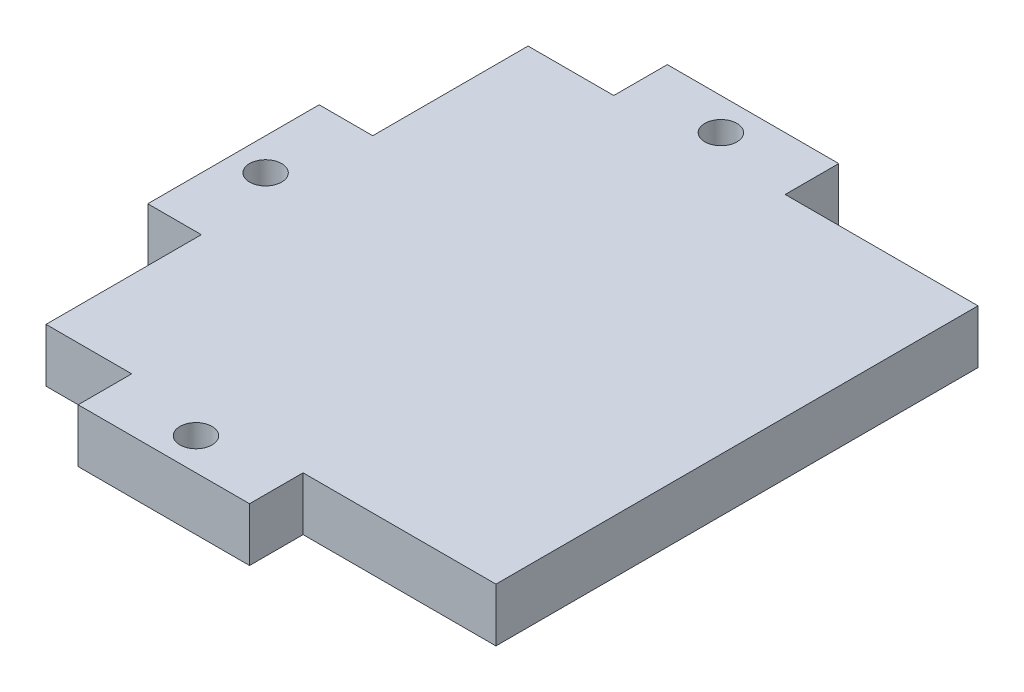
SolidWorks part; units mm, degrees
material "Trupan"
ref_plane "Alzado" through (0, 0, 0) normal (0, 0, 1) x (1, 0, 0)
ref_plane "Planta" through (0, 0, 0) normal (0, 1, 0) x (1, 0, 0)
ref_plane "Vista lateral" through (0, 0, 0) normal (1, 0, 0) x (0, 0, -1)
sketch "Croquis1" plane through (0, 0, 0) normal (0, 1, 0) x (1, 0, 0)
  line L1 (16, -22.5) -> (-16, -22.5)
  line L2 (16, -22.5) -> (16, 22.5)
  line L3 (16, 22.5) -> (-16, 22.5)
  line L4 (-16, -22.5) -> (-16, 22.5)
  line L5 (16, -22.5) -> (-16, 22.5) construction
  line L6 (16, 22.5) -> (-16, -22.5) construction
  point P0 (0, 0)
  dimension "D1" = 32
  dimension "D2" = 45
extrude "Saliente-Extruir1" add sketch "Croquis1" along normal blind 5
sketch "Croquis2" plane through (0, 5, 0) normal (0, 1, 0) x (1, 0, 0)
  line L0 (16, 22.5) -> (-16, 22.5) construction
  line L1 (8, 17.5) -> (-8, 17.5)
  line L2 (8, 17.5) -> (8, 27.5)
  line L3 (8, 27.5) -> (-8, 27.5)
  line L4 (-8, 17.5) -> (-8, 27.5)
  line L5 (8, 17.5) -> (-8, 27.5) construction
  line L6 (8, 27.5) -> (-8, 17.5) construction
  point P0 (0, 22.5)
  dimension "D1" = 5
  dimension "D2" = 16
extrude "Saliente-Extruir2" add sketch "Croquis2" against normal through all
sketch "Croquis3" plane through (0, 5, 0) normal (0, 1, 0) x (1, 0, 0)
  line L0 (8, 27.5) -> (-8, 27.5) construction
  circle A0 centre (0, 24.5) radius 1.5
  dimension "D2" = 3
  dimension "D1" = 3
extrude "Cortar-Extruir1" cut sketch "Croquis3" against normal through all
mirror "Simetría1" about plane through (0, 0, 0) normal (0, 0, 1) of "Saliente-Extruir2", "Cortar-Extruir1"
sketch "Croquis4" plane through (0, 5, 0) normal (0, 1, 0) x (1, 0, 0)
  line L0 (-16, 22.5) -> (-16, -22.5) construction
  line L1 (-11, -8) -> (-21, -8)
  line L2 (-11, -8) -> (-11, 8)
  line L3 (-11, 8) -> (-21, 8)
  line L4 (-21, -8) -> (-21, 8)
  line L5 (-11, -8) -> (-21, 8) construction
  line L6 (-11, 8) -> (-21, -8) construction
  point P0 (-16, 0)
  dimension "D1" = 16
  dimension "D2" = 5
extrude "Saliente-Extruir3" add sketch "Croquis4" against normal through all
sketch "Croquis5" plane through (0, 5, 0) normal (0, 1, 0) x (1, 0, 0)
  line L0 (-21, 8) -> (-21, -8) construction
  line L1 (-21, -8) -> (-16, -8) construction
  circle A0 centre (-18, 0) radius 1.5
  dimension "D2" = 3
  dimension "D1" = 3
  dimension "D3" = 8
extrude "Cortar-Extruir2" cut sketch "Croquis5" against normal through all
sketch "Croquis6" plane through (0, 5, 0) normal (0, 1, 0) x (1, 0, 0)
  line L1 (16, 22.5) -> (26, 22.5)
  line L2 (16, 22.5) -> (16, -22.5)
  line L3 (16, -22.5) -> (26, -22.5)
  line L4 (26, 22.5) -> (26, -22.5)
  dimension "D1" = 10
extrude "Saliente-Extruir4" add sketch "Croquis6" against normal blind 5
